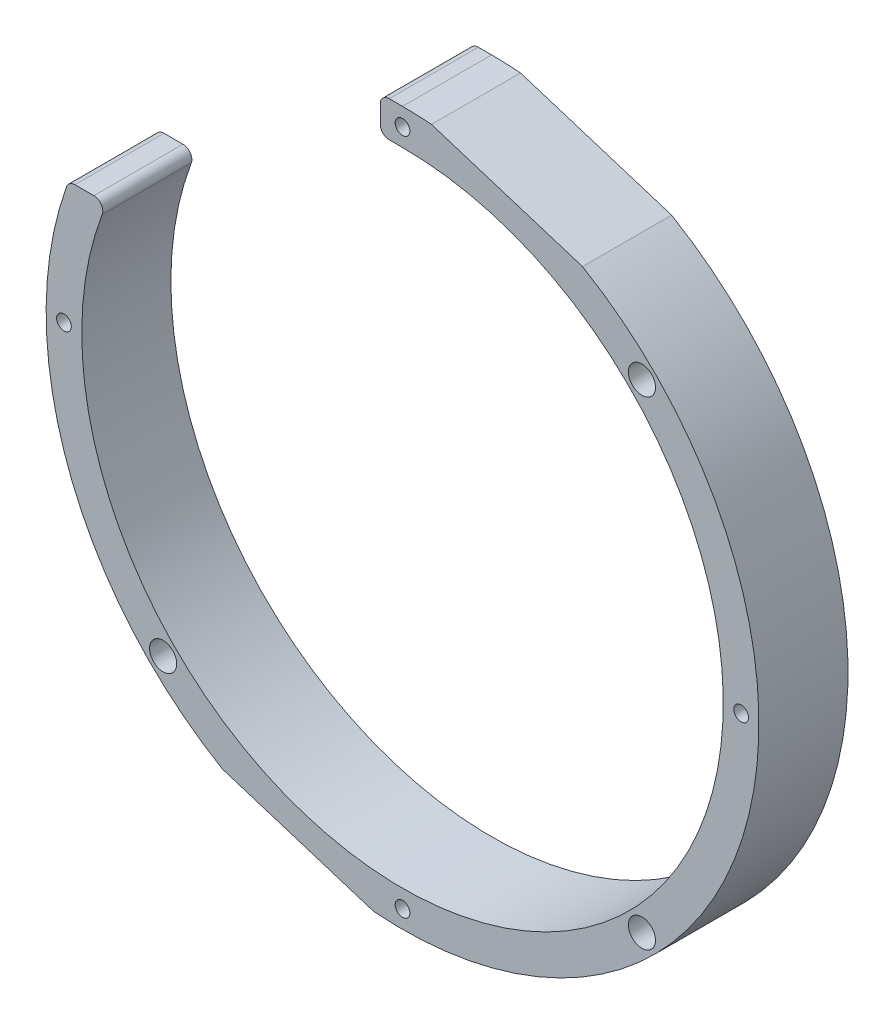
SolidWorks part; units mm, degrees
material "Acrylic (Medium-high impact) 丙烯酸纤维"
ref_plane "前视基准面" through (0, 0, 0) normal (0, 0, 1) x (1, 0, 0)
ref_plane "上视基准面" through (0, 0, 0) normal (0, 1, 0) x (1, 0, 0)
ref_plane "右视基准面" through (0, 0, 0) normal (1, 0, 0) x (0, 0, -1)
sketch "草图1" plane through (0, 0, 0) normal (0, 0, 1) x (1, 0, 0)
  circle A0 centre (0, 0) radius 72
  circle A1 centre (0, 0) radius 80
  dimension "D1" = 144
  dimension "D2" = 8
extrude "凸台-拉伸1" add sketch "草图1" along normal blind 20
sketch "草图2" plane through (0, 0, 20) normal (0, 0, 1) x (1, 0, 0)
  line L0 (0, 80) -> (-88.5005, 80)
  line L1 (0, 28) -> (-88.5005, 28)
  line L2 (0, 80) -> (0, 28)
  line L3 (-88.5005, 80) -> (-88.5005, 28)
  circle A0 centre (0, 0) radius 80 construction
  dimension "D2" = 88.5005
  dimension "D1" = 52
extrude "切除-拉伸1" cut sketch "草图2" against normal blind 20
sketch "草图3" plane through (0, 0, 20) normal (0, 0, 1) x (1, 0, 0)
  line L1 (0, 72) -> (-5, 72)
  line L2 (0, 72) -> (0, 80)
  line L3 (0, 80) -> (-5, 80)
  line L4 (-5, 72) -> (-5, 80)
  arc A0 (-74.94, 28) -> (0, 80) centre (0, 0) ccw construction
  dimension "D1" = 5
extrude "凸台-拉伸2" add sketch "草图3" against normal up to surface (20 mm away) up to face at (3.6926, -5.4317, 0)
fillet "圆角1" radius 2 4 edges at (-66.3325, 28, 10) (-74.94, 28, 10) (-5, 80, 10) (-5, 72, 10)
sketch "草图4" plane through (0, 0, 20) normal (0, 0, 1) x (1, 0, 0)
  line L0 (0, 76) -> (0, 0) construction
  line L1 (0, 0) -> (0, -76) construction
  line L2 (0, 0) -> (76, 0) construction
  circle A4 centre (-76, 0) radius 1.65
  circle A5 centre (0, -76) radius 1.65
  circle A6 centre (76, 0) radius 1.65
  circle A7 centre (0, 76) radius 1.65
  dimension "D1" = 3.3
  dimension "D2" = 76
  dimension "D3" = 76
extrude "切除-拉伸2" cut sketch "草图4" against normal blind 20
sketch "草图5" plane through (0, 0, 20) normal (0, 0, 1) x (1, 0, 0)
  line L0 (0, -80) -> (0, 0) construction
  line L1 (0, 0) -> (53.7401, 53.7401) construction
  line L2 (0, 0) -> (53.7401, -53.7401) construction
  arc A0 (-75.4247, 26.6667) -> (0, 80) centre (0, 0) ccw construction
  circle A1 centre (53.7401, 53.7401) radius 3.05
  arc A2 (-67.4095, 25.2973) -> (0, 72) centre (0, 0) ccw construction
  circle A3 centre (53.7401, -53.7401) radius 3.05
  circle A4 centre (-53.7401, -53.7401) radius 3.05
  dimension "D2" = 6.1
  dimension "D5" = 6.1
  dimension "D1" = 135
  dimension "D3" = 4
  dimension "D4" = 45
  dimension "D6" = 4
extrude "切除-拉伸3" cut sketch "草图5" against normal blind 30
sketch "草图7" plane through (0, 0, 20) normal (0, 0, 1) x (1, 0, 0)
  line L0 (51.9117, -98.1334) -> (-75.813, -57.8951) construction
  line L1 (6.8691, -83.9432) -> (-55.1468, -64.4058)
  line L2 (-28.938, 90.8958) -> (98.7867, 50.6575) construction
  line L3 (-8.2718, 84.3851) -> (53.7441, 64.8477)
  line L4 (-55.1468, -64.4058) -> (-66.1914, -99.4636)
  line L5 (-66.1914, -99.4636) -> (-4.1755, -119.0011)
  line L6 (-4.1755, -119.0011) -> (6.8691, -83.9432)
  line L7 (53.7441, 64.8477) -> (64.7887, 99.9055)
  line L8 (64.7887, 99.9055) -> (2.7728, 119.443)
  line L9 (2.7728, 119.443) -> (-8.2718, 84.3851)
extrude "切除-拉伸4" cut sketch "草图7" against normal blind 50
